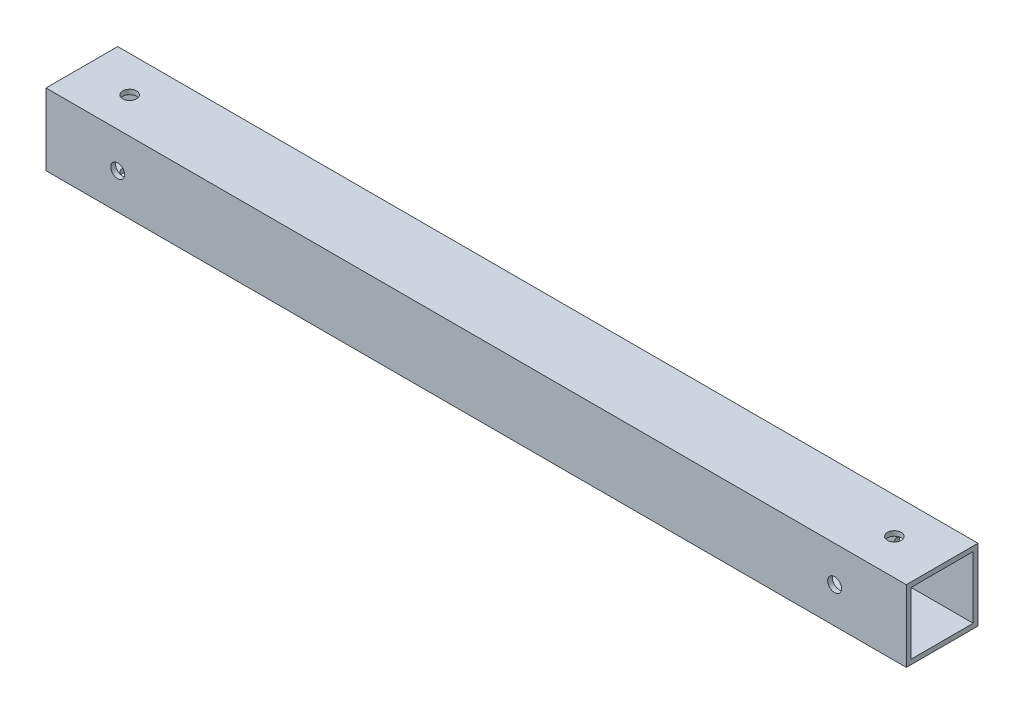
SolidWorks part; units mm, degrees
material "6061 合金"
ref_plane "前视基准面" through (0, 0, 0) normal (0, 0, 1) x (1, 0, 0)
ref_plane "上视基准面" through (0, 0, 0) normal (0, 1, 0) x (1, 0, 0)
ref_plane "右视基准面" through (0, 0, 0) normal (1, 0, 0) x (0, 0, -1)
other "Configuration Table"
sketch "草图1" plane through (0, 0, 0) normal (1, 0, 0) x (0, 0, -1)
  line L0 (-6.5, -6.5) -> (-6.5, 6.5)
  line L1 (-7.5, -7.5) -> (7.5, -7.5)
  line L2 (-7.5, -7.5) -> (-7.5, 7.5)
  line L3 (-7.5, 7.5) -> (7.5, 7.5)
  line L4 (7.5, -7.5) -> (7.5, 7.5)
  line L5 (-7.5, -7.5) -> (7.5, 7.5) construction
  line L6 (-7.5, 7.5) -> (7.5, -7.5) construction
  line L7 (-6.5, 6.5) -> (6.5, 6.5)
  line L8 (6.5, -6.5) -> (6.5, 6.5)
  line L9 (-6.5, -6.5) -> (6.5, -6.5)
  point P0 (0, 0)
  dimension "D1" = 15
  dimension "D2" = 15
  dimension "D3" = 1
extrude "凸台-拉伸1" add sketch "草图1" along normal blind 180
sketch "草图2" plane through (0, 7.5, 0) normal (0, 1, 0) x (1, 0, 0)
  circle A0 centre (170, 0) radius 1.65 construction
  circle A1 centre (10, 0) radius 1.65 construction
  circle A2 centre (170, 0) radius 1.65 construction
  circle A3 centre (10, 0) radius 1.65 construction
  circle A4 centre (10, 0) radius 1.45
  circle A5 centre (170, 0) radius 1.45
  dimension "D1" = 2.9
  dimension "D2" = 2.9
extrude "切除-拉伸1" cut sketch "草图2" against normal through all
sketch "草图3" plane through (0, 0, 7.5) normal (0, 0, 1) x (1, 0, 0)
  circle A0 centre (165, 0) radius 1.65 construction
  circle A1 centre (15, 0) radius 1.65 construction
  circle A2 centre (165, 0) radius 1.65 construction
  circle A3 centre (15, 0) radius 1.65 construction
  circle A4 centre (15, 0) radius 1.45
  circle A5 centre (165, 0) radius 1.45
  dimension "D1" = 2.9
  dimension "D2" = 2.9
extrude "切除-拉伸2" cut sketch "草图3" against normal through all
